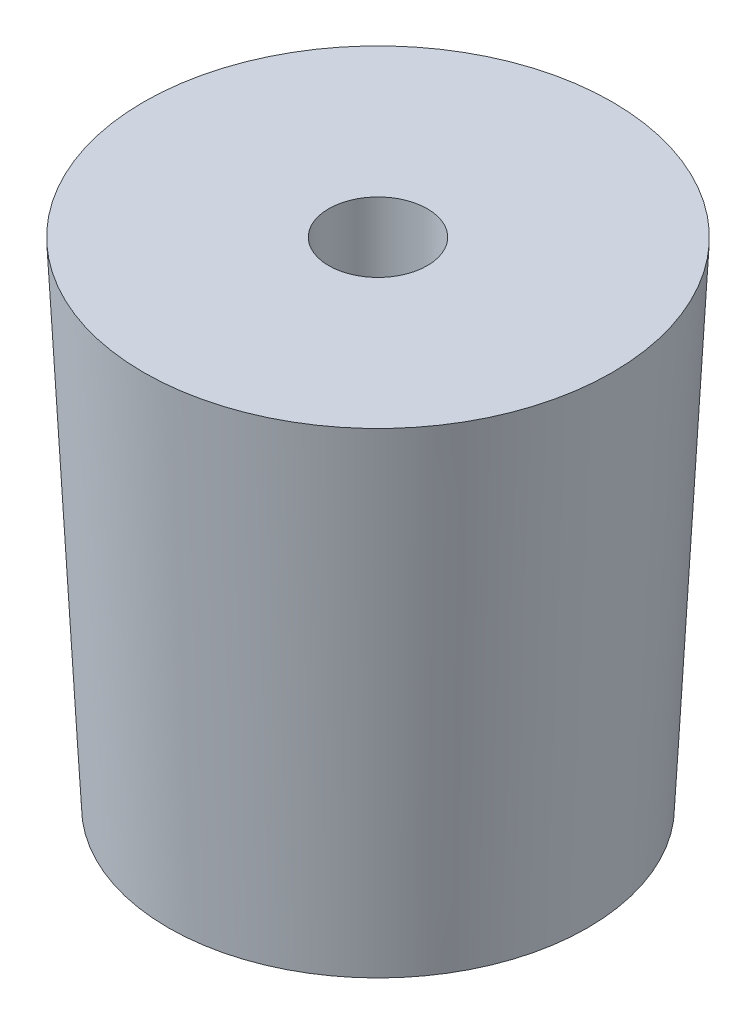
SolidWorks part; units mm, degrees
ref_plane "Front Plane" through (0, 0, 0) normal (0, 0, 1) x (1, 0, 0)
ref_plane "Top Plane" through (0, 0, 0) normal (0, 1, 0) x (1, 0, 0)
ref_plane "Right Plane" through (0, 0, 0) normal (1, 0, 0) x (0, 0, -1)
sketch "Sketch1" plane through (0, 0, 0) normal (0, 1, 0) x (1, 0, 0)
  circle A0 centre (0, 0) radius 9.5
  circle A1 centre (0, 0) radius 2
  dimension "D1" = 19
  dimension "D2" = 4
extrude "Boss-Extrude1" add sketch "Sketch1" along normal blind 20
sketch "Sketch2" plane through (0, 0, 0) normal (0, 0, 1) x (1, 0, 0)
  line L0 (-9.5, 20) -> (-8.5, 0)
  line L1 (-9.5, 0) -> (9.5, 0) construction
  line L2 (-8.5, 0) -> (-9.5, 0)
  line L3 (-9.5, 0) -> (-9.5, 20)
  line L4 (0, 20) -> (0, 0) construction
  line L5 (2, 20) -> (-2, 20) construction
  dimension "D1" = 8.5
revolve "Cut-Revolve1" cut sketch "Sketch2" angle 360 about L4
sketch "Sketch3" plane through (0, 0, 0) normal (0, -1, 0) x (1, 0, 0)
  circle A0 centre (0, 0) radius 5
  dimension "D1" = 10
extrude "Cut-Extrude1" cut sketch "Sketch3" against normal blind 10
